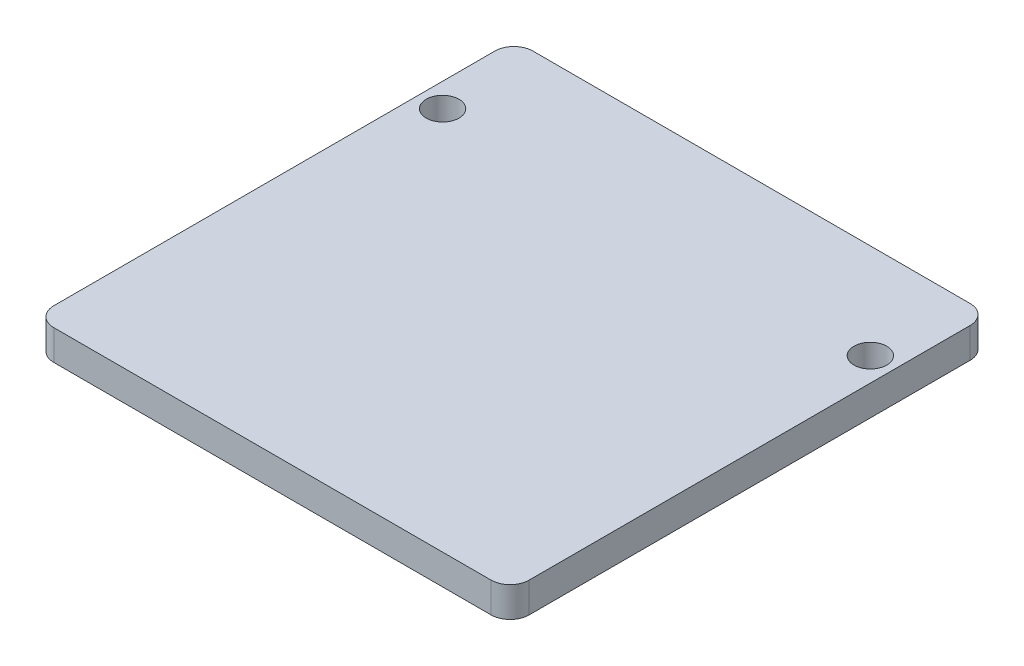
SolidWorks part; units mm, degrees
ref_plane "Front Plane" through (0, 0, 0) normal (0, 0, 1) x (1, 0, 0)
ref_plane "Top Plane" through (0, 0, 0) normal (0, 1, 0) x (1, 0, 0)
ref_plane "Right Plane" through (0, 0, 0) normal (1, 0, 0) x (0, 0, -1)
sketch "Sketch1" plane through (0, 0, 0) normal (0, 1, 0) x (1, 0, 0)
  line L0 (0, 0) -> (45, 0) construction
  line L2 (-2.5, 10) -> (47.5, 10)
  line L3 (-2.5, 10) -> (-2.5, -15.4)
  line L4 (-2.5, -15.4) -> (47.5, -15.4)
  line L5 (47.5, 10) -> (47.5, -15.4)
  line L6 (-2.5, -15.4) -> (47.5, -15.4)
  line L7 (-2.5, -15.4) -> (-2.5, -40.4)
  line L8 (-2.5, -40.4) -> (47.5, -40.4)
  line L9 (47.5, -15.4) -> (47.5, -40.4)
  circle A0 centre (0, 0) radius 1.725
  circle A1 centre (45, 0) radius 1.725
  point P9 (0, 0)
  point P10 (44.6447, 5.6439)
  point P11 (0, 0)
  point P14 (-2.3399, 5.6439)
  point P15 (0, 0)
  dimension "D2" = 3.45
  dimension "D1" = 45
  dimension "D3" = 50
  dimension "D5" = 25.4
  dimension "D6" = 25
  dimension "D4" = 10
  dimension "D7" = 2.5
extrude "Boss-Extrude1" add sketch "Sketch1" along normal blind 3.175
fillet "Fillet1" radius 2 4 edges at (47.5, 1.5875, -10) (-2.5, 1.5875, -10) (47.5, 1.5875, 40.4) (-2.5, 1.5875, 40.4)
equation "\"D7@Sketch1\"=(\"D3@Sketch1\"-\"D1@Sketch1\")/2"
